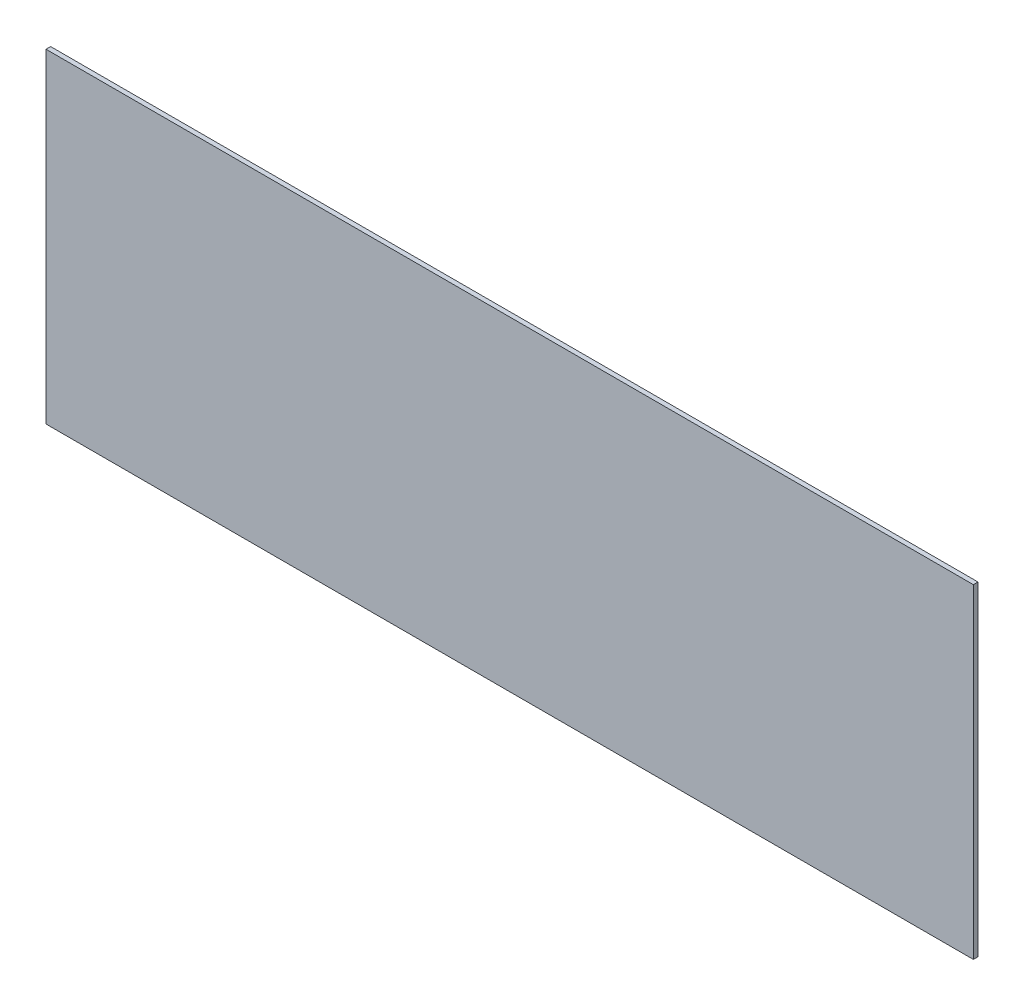
SolidWorks part; units mm, degrees
material "Plain Carbon Steel"
ref_plane "Front Plane" through (0, 0, 0) normal (0, 0, 1) x (1, 0, 0)
ref_plane "Top Plane" through (0, 0, 0) normal (0, 1, 0) x (1, 0, 0)
ref_plane "Right Plane" through (0, 0, 0) normal (1, 0, 0) x (0, 0, -1)
sketch "Sketch1" plane through (0, 0, 0) normal (0, 0, 1) x (1, 0, 0)
  line L1 (-100, 35) -> (100, 35)
  line L2 (-100, 35) -> (-100, -35)
  line L3 (-100, -35) -> (100, -35)
  line L4 (100, 35) -> (100, -35)
  line L5 (-100, 35) -> (100, -35) construction
  line L6 (-100, -35) -> (100, 35) construction
  point P0 (0, 0)
  dimension "D1" = 200
  dimension "D2" = 70
extrude "Boss-Extrude1" add sketch "Sketch1" along normal blind 1
